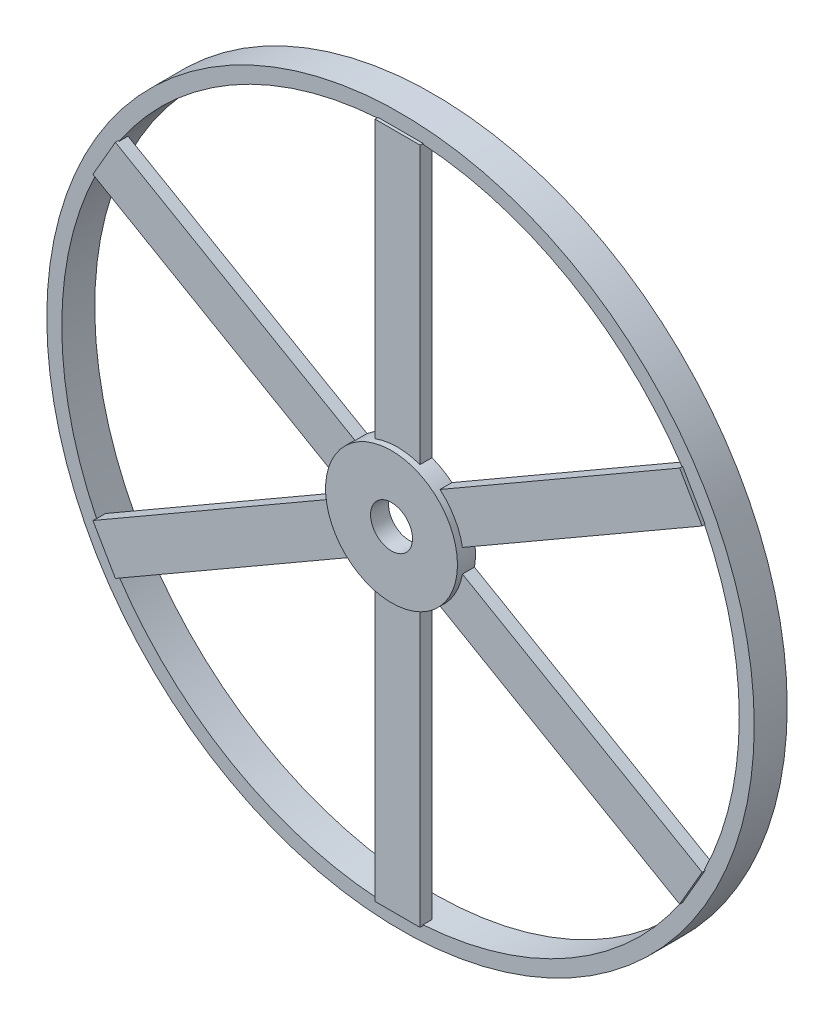
SolidWorks part; units mm, degrees
ref_plane "前视基准面" through (0, 0, 0) normal (0, 0, 1) x (1, 0, 0)
ref_plane "上视基准面" through (0, 0, 0) normal (0, 1, 0) x (1, 0, 0)
ref_plane "右视基准面" through (0, 0, 0) normal (1, 0, 0) x (0, 0, -1)
other "Configuration Table"
sketch "草图1" plane through (0, 0, 0) normal (0, 0, 1) x (1, 0, 0)
  circle A0 centre (0, 0) radius 118 construction
  circle A1 centre (0, 0) radius 118
extrude "拉伸-薄壁1" add sketch "草图1" along normal blind 11 thin thin type one direction reverse wall 5
sketch "草图2" plane through (0, 0, 11) normal (0, 0, 1) x (1, 0, 0)
  line L0 (0, 113) -> (0, 14.8829)
  circle A0 centre (0, 0) radius 113 construction
extrude "拉伸-薄壁2" add sketch "草图2" along normal blind 1 and the other way blind 3 thin thin type mid plane wall 15
pattern_circular "阵列(圆周)1" count 6 over 360 about axis through (0, 0, 0) along (0, 0, 1) of "拉伸-薄壁2"
sketch "草图3" plane through (0, 0, 11) normal (0, 0, 1) x (1, 0, 0)
  circle A0 centre (0, 0) radius 7
  dimension "D1" = 14
extrude "拉伸-薄壁3" add sketch "草图3" along normal blind 3 and the other way blind 3 thin
